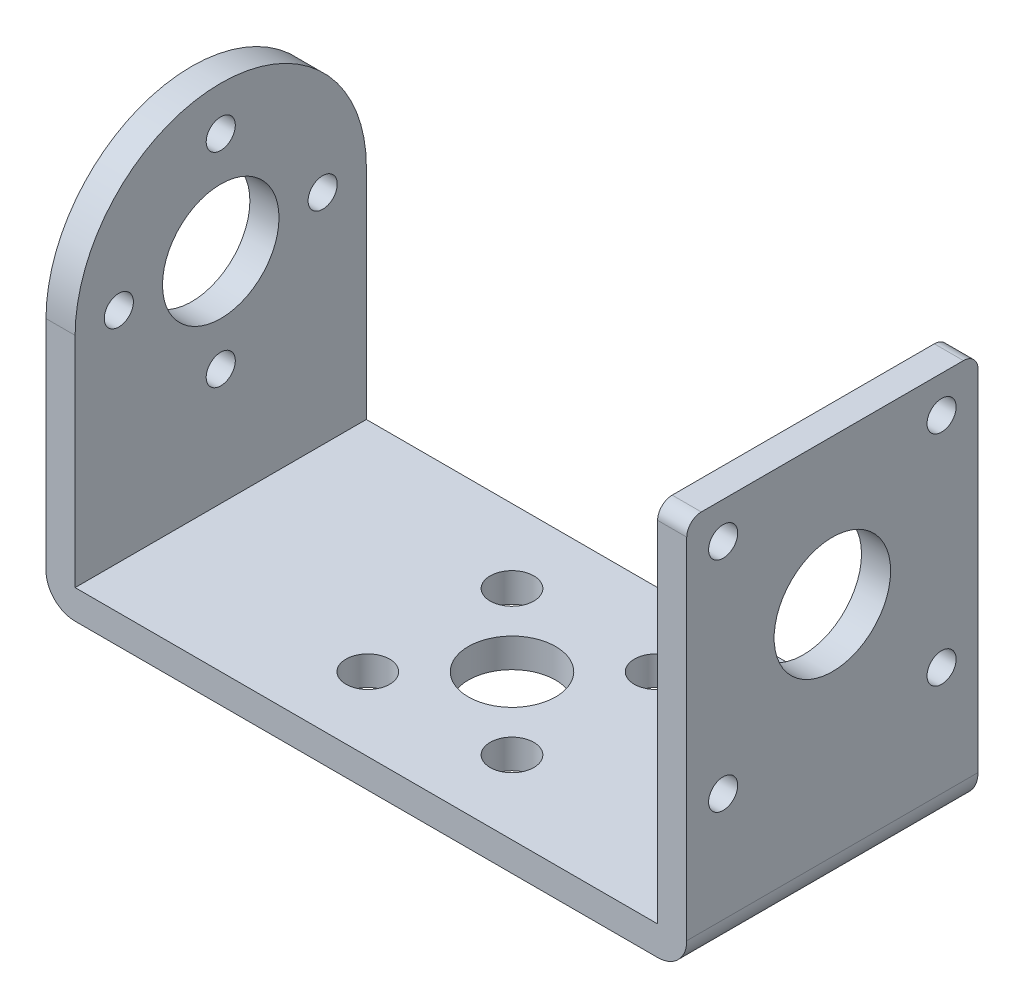
SolidWorks part; units mm, degrees
material "1060-H12"
ref_plane "前视基准面" through (0, 0, 0) normal (0, 0, 1) x (1, 0, 0)
ref_plane "上视基准面" through (0, 0, 0) normal (0, 1, 0) x (1, 0, 0)
ref_plane "右视基准面" through (0, 0, 0) normal (1, 0, 0) x (0, 0, -1)
sketch "草图1" plane through (0, 0, 0) normal (0, 1, 0) x (1, 0, 0)
  line L0 (20, 0) -> (-20, 0) construction
  line L1 (-20, 10) -> (20, 10)
  line L2 (-20, 10) -> (-20, -10)
  line L3 (-20, -10) -> (20, -10)
  line L4 (20, 10) -> (20, -10)
  line L5 (-20, 10) -> (20, -10) construction
  line L6 (-20, -10) -> (20, 10) construction
  line L7 (0, 10) -> (0, -10) construction
  circle A0 centre (0, 0) radius 7 construction
  circle A1 centre (0, 0) radius 3
  circle A2 centre (-4.9497, -4.9497) radius 1.5
  circle A3 centre (-4.9497, 4.9497) radius 1.5
  circle A4 centre (4.9497, 4.9497) radius 1.5
  circle A5 centre (4.9497, -4.9497) radius 1.5
  point P0 (0, 0)
  point P20 (0, 0)
  point P24 (0, 0)
  point P26 (0, 0)
  dimension "D3" = 14
  dimension "D4" = 6
  dimension "D5" = 3
  dimension "D1" = 20
  dimension "D2" = 40
  dimension "D6" = 4
extrude "凸台-拉伸1" add sketch "草图1" along normal blind 2
sketch "草图2" plane through (0, 0, 0) normal (0, 1, 0) x (1, 0, 0)
  line L0 (-20, -10) -> (20, -10) construction
  line L1 (20, 10) -> (22, 10)
  line L2 (20, 10) -> (20, -10)
  line L3 (20, -10) -> (22, -10)
  line L4 (22, 10) -> (22, -10)
  line L5 (-20, 10) -> (-22, 10)
  line L6 (-20, 10) -> (-20, -10)
  line L7 (-20, -10) -> (-22, -10)
  line L8 (-22, 10) -> (-22, -10)
  dimension "D1" = 2
  dimension "D2" = 2
extrude "凸台-拉伸2" add sketch "草图2" along normal blind 27
sketch "草图3" plane through (0, 0, 0) normal (1, 0, 0) x (0, 0, -1)
  line L0 (10, 2) -> (-10, 2) construction
  line L1 (-10, 17) -> (-10, 27)
  line L2 (-10, 27) -> (10, 27)
  line L3 (10, 27) -> (10, 17)
  circle A0 centre (0, 17) radius 7 construction
  circle A1 centre (0, 17) radius 4
  circle A2 centre (0, 10) radius 1
  circle A7 centre (0, 17) radius 10
  circle A8 centre (-7, 17) radius 1
  circle A9 centre (0, 24) radius 1
  circle A10 centre (7, 17) radius 1
  point P22 (0, 32)
  point P27 (0, 17)
  dimension "D1" = 14
  dimension "D2" = 8
  dimension "D5" = 2
  dimension "D8" = 20
  dimension "D3" = 15
  dimension "D7" = 4
extrude "切除-拉伸1" cut sketch "草图3" against normal blind 22 contours A7 L2 L1 | A7 L3 L2 | A1 | A2 | A10 | A9 | A8
sketch "草图4" plane through (0, 0, 0) normal (1, 0, 0) x (0, 0, -1)
  line L1 (-10, 17) -> (10, 17) construction
  line L4 (0, 27) -> (0, 0) construction
  circle A0 centre (0, 17) radius 4
  arc A4 (10, 17) -> (-10, 17) centre (0, 17) ccw construction
  circle A6 centre (-7.5, 24.5) radius 1
  circle A7 centre (-7.5, 9.5) radius 1
  circle A8 centre (7.5, 9.5) radius 1
  circle A9 centre (7.5, 24.5) radius 1
  point P8 (0, 17)
  dimension "D4" = 7.5
  dimension "D6" = 8
  dimension "D2" = 2
  dimension "D3" = 7.5
extrude "切除-拉伸2" cut sketch "草图4" along normal through all
fillet "圆角1" radius 2 2 edges at (-22, 0, 0) (22, 0, 0)
fillet "圆角2" radius 1 2 edges at (21, 27, 10) (21, 27, -10)
